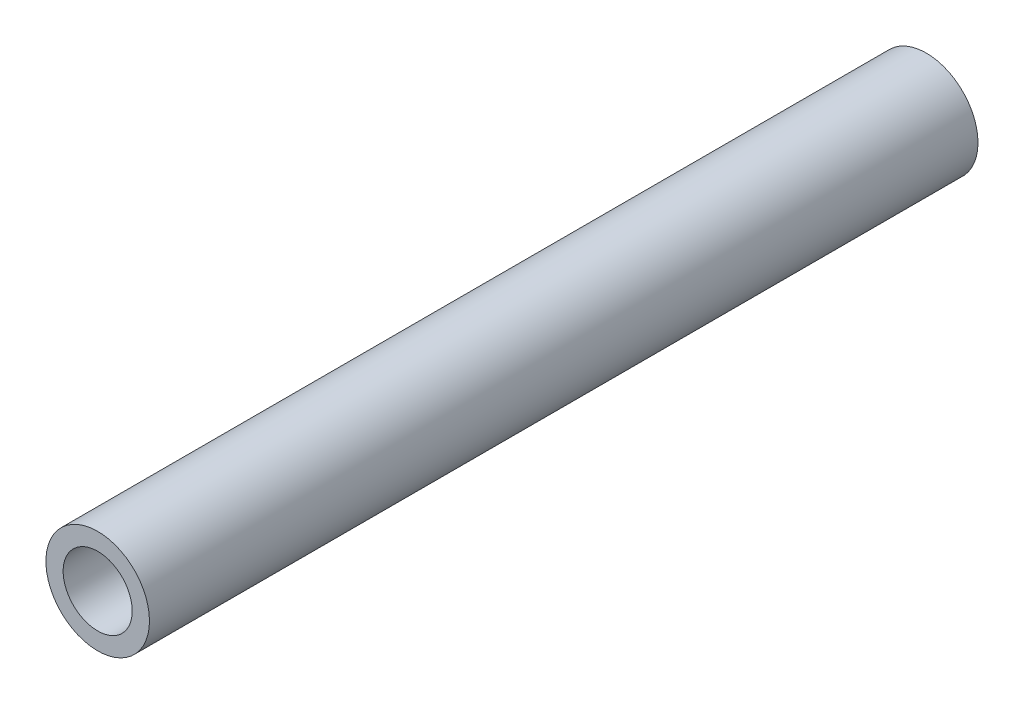
SolidWorks part; units mm, degrees
ref_plane "前视基准面" through (0, 0, 0) normal (0, 0, 1) x (1, 0, 0)
ref_plane "上视基准面" through (0, 0, 0) normal (0, 1, 0) x (1, 0, 0)
ref_plane "右视基准面" through (0, 0, 0) normal (1, 0, 0) x (0, 0, -1)
sketch "草图1" plane through (0, 0, 0) normal (0, 0, 1) x (1, 0, 0)
  circle A0 centre (0, 0) radius 7.5
  circle A1 centre (0, 0) radius 5
  dimension "D1" = 10
  dimension "D2" = 15
extrude "凸台-拉伸1" add sketch "草图1" along normal blind 120
